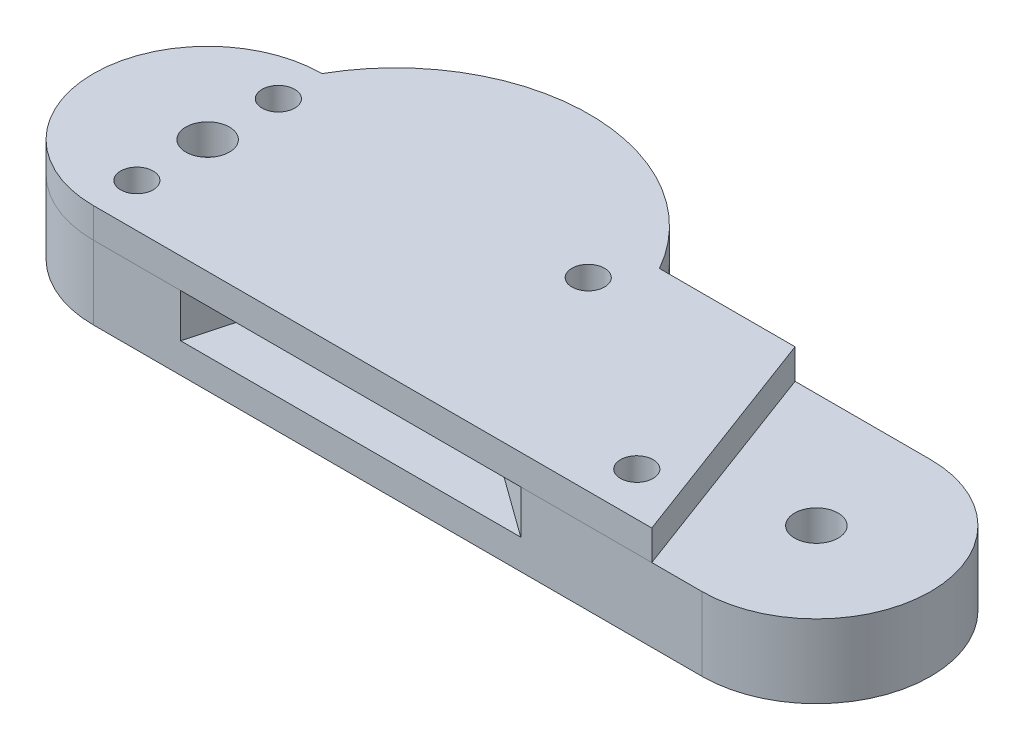
SolidWorks part; units mm, degrees
ref_plane "Front Plane" through (0, 0, 0) normal (0, 0, 1) x (1, 0, 0)
ref_plane "Top Plane" through (0, 0, 0) normal (0, 1, 0) x (1, 0, 0)
ref_plane "Right Plane" through (0, 0, 0) normal (1, 0, 0) x (0, 0, -1)
sketch "Sketch1" plane through (0, 0, 0) normal (0, 1, 0) x (1, 0, 0)
  line L0 (0, -10.5004) -> (-55.9305, -10.5004)
  line L1 (0, 10.5004) -> (-55.9305, 10.5004)
  line L5 (0, 11.5004) -> (-55.9305, 11.5004) construction
  line L6 (0, -11.5004) -> (-55.9305, -11.5004) construction
  circle A0 centre (0, 0) radius 2
  arc A1 (0, -10.5004) -> (0, 10.5004) centre (0, 0) ccw
  arc A2 (-55.9305, 10.5004) -> (-55.9305, -10.5004) centre (-55.9305, 0) ccw
  circle A3 centre (-55.9305, 0) radius 2
  arc A7 (0, -11.5004) -> (0, 11.5004) centre (0, 0) ccw construction
  arc A8 (-55.9305, 11.5004) -> (-55.9305, -11.5004) centre (-55.9305, 0) ccw construction
  arc A9 (-67.2423, -5.04) -> (-54.9145, -15.6487) centre (-55.7741, -4.1805) ccw construction
  arc A10 (-55.9305, 10.5004) -> (-55.9305, -10.5004) centre (-55.9305, 0) ccw construction
  circle A11 centre (0, 0) radius 67.4309 construction
  arc A12 (-59.8966, 30.973) -> (-67.2423, -5.04) centre (0, 0) ccw construction
  dimension "D1" = 4
  dimension "D2" = 1
  dimension "D3" = 4
extrude "Boss-Extrude1" add sketch "Sketch1" along normal mid plane 9.5
sketch "Sketch3" plane through (0, 0, 0) normal (0, 1, 0) x (1, 0, 0)
  line L0 (0, 0) -> (-47.1525, -15.3208) construction
  line L1 (0, 0) -> (24.7895, -42.9367) construction
  line L2 (0, 0) -> (-55.9305, 0) construction
  line L3 (24.7895, -42.9367) -> (-41.5934, 5.0595) construction
  line L4 (-41.5934, 5.0595) -> (-47.1525, -15.3208) construction
  line L5 (-41.5934, 5.0595) -> (-37.6461, 19.5308) construction
  line L6 (-41.5934, 5.0595) -> (-53.749, 13.8482) construction
  line L7 (22.8477, -44.0007) -> (-38.0092, 0) construction
  line L8 (-35.7518, 18.8753) -> (-39.2995, 5.869)
  line L9 (-43.8873, 4.25) -> (-54.8123, 12.149)
  line L11 (26.6452, -41.8104) -> (-39.2995, 5.869)
  line L12 (-39.6108, 19.9279) -> (-42.7627, 8.3729) construction
  line L13 (-42.7627, 8.3729) -> (-52.4686, 15.3905) construction
  line L14 (-40.9004, 0) -> (-45.9674, -18.5763) construction
  line L15 (-43.8873, 4.25) -> (-48.2065, -11.585)
  line L18 (-40.4216, 6.6802) -> (-50.8477, 14.2185) construction
  line L20 (-41.5934, 5.0595) -> (-52.0196, 12.5978) construction
  line L21 (-42.7652, 3.4387) -> (-53.1914, 10.977) construction
  line L23 (-43.5229, 5.5858) -> (-49.082, -14.7945) construction
  line L26 (-39.6639, 4.5332) -> (-45.223, -15.8471) construction
  line L27 (25.9613, -41.316) -> (-40.4216, 6.6802) construction
  line L28 (23.6177, -44.5574) -> (-42.7652, 3.4387) construction
  arc A1 (-48.2065, -11.585) -> (26.6452, -41.8104) centre (0, 0) ccw
  arc A4 (-55.9305, 10.5004) -> (-55.9305, -10.5004) centre (-55.9305, 0) ccw construction
  arc A7 (-35.7518, 18.8753) -> (-54.8123, 12.149) centre (-41.5934, 5.0595) ccw
  dimension "D1" = 99.1581
  dimension "D3" = 120
  dimension "D6" = 30
  dimension "D2" = 18
  dimension "D4" = 2
  dimension "D5" = 2
extrude "Cut-Extrude1" cut sketch "Sketch3" against normal mid plane 4
sketch "Sketch5" plane through (0, 0, 0) normal (0, 1, 0) x (1, 0, 0)
  line L0 (-40.4241, 1.7461) -> (-52.5322, 10.5004) construction
  line L1 (-40.4241, 1.7461) -> (-35.7382, 18.9254) construction
  line L2 (-52.5322, 10.5004) -> (-43.8873, 4.25) construction
  line L3 (-39.2995, 5.869) -> (-38.0362, 10.5004) construction
  line L4 (-55.9305, 10.5004) -> (-24.9177, 10.5004)
  line L5 (0, 10.5004) -> (-55.9305, 10.5004) construction
  circle A0 centre (-40.4241, 1.7461) radius 17.807
extrude "Boss-Extrude2" add sketch "Sketch5" along normal up to surface and the other way up to surface
sketch "Sketch6" plane through (0, 0, 0) normal (0, 1, 0) x (1, 0, 0)
  line L0 (-39.2995, 5.869) -> (-16.6593, -10.5004)
  line L1 (-47.9107, -10.5004) -> (-43.8873, 4.25)
  line L2 (-43.8873, 4.25) -> (-54.8544, 12.1794)
  line L3 (-39.2995, 5.869) -> (-35.7382, 18.9254)
  line L4 (-16.6593, -10.5004) -> (-39.2995, 5.869) construction
  line L5 (-43.8873, 4.25) -> (-47.9107, -10.5004) construction
  line L6 (-52.5322, 10.5004) -> (-43.8873, 4.25) construction
  line L7 (-39.2995, 5.869) -> (-38.0362, 10.5004) construction
  line L8 (-55.9305, -10.5004) -> (0, -10.5004) construction
  line L9 (-16.6593, -10.5004) -> (-47.9107, -10.5004)
  arc A0 (-24.9177, 10.5004) -> (-55.9305, 10.5004) centre (-40.4241, 1.7461) ccw construction
  arc A1 (-35.7382, 18.9254) -> (-54.8544, 12.1794) centre (-40.4241, 1.7461) ccw
extrude "Cut-Extrude2" cut sketch "Sketch6" against normal mid plane 4
sketch "Sketch7" plane through (0, -4.75, 0) normal (0, -1, 0) x (1, 0, 0)
  line L0 (0, 0) -> (4.5965, 4.5965) construction
  line L1 (0, 0) -> (6.5004, 0) construction
  line L4 (0, 6.5004) -> (-55.9305, 6.5004)
  line L5 (-27.4616, -6.5004) -> (0, -6.5004)
  line L6 (0, 6.5004) -> (-55.9305, 6.5004) construction
  line L7 (-55.9305, -6.5004) -> (0, -6.5004) construction
  circle A3 centre (-27.4616, -6.5004) radius 1.5
  circle A4 centre (0, -6.5004) radius 1.5 construction
  circle A5 centre (4.5965, 4.5965) radius 1.5 construction
  arc A6 (0, -6.5004) -> (0, 6.5004) centre (0, 0) ccw
  arc A7 (-55.9305, 6.5004) -> (-53.5442, -6.0466) centre (-55.9305, 0) ccw
  arc A8 (-53.5442, -6.0466) -> (-27.4616, -6.5004) centre (-40.4241, -1.7461) ccw
  arc A9 (0, -6.5004) -> (0, 6.5004) centre (0, 0) ccw construction
  arc A10 (-55.9305, 6.5004) -> (-53.5442, -6.0466) centre (-55.9305, 0) ccw construction
  arc A11 (-53.5442, -6.0466) -> (-27.4616, -6.5004) centre (-40.4241, -1.7461) ccw construction
  circle A12 centre (-10, 6.5004) radius 1.5
  circle A13 centre (-55.9305, 6.5004) radius 1.5
  circle A14 centre (-55.9305, -6.5004) radius 1.5
  dimension "D4" = 3
  dimension "D2" = 10
  dimension "D3" = 45
  dimension "D1" = 4
extrude "Cut-Extrude3" cut sketch "Sketch7" against normal through all
sketch "Sketch8" plane through (0, -4.75, 0) normal (0, -1, 0) x (1, 0, 0)
  circle A0 centre (-55.9305, 6.5004) radius 2.75
  circle A1 centre (-55.9305, -6.5004) radius 2.75
  circle A2 centre (-27.4616, -6.5004) radius 2.75
  circle A3 centre (-10, 6.5004) radius 2.75
  dimension "D1" = 5.5
extrude "Cut-Extrude4" cut sketch "Sketch8" against normal blind 3.2
ref_plane "Plane1" through (0, 2, 0) normal (0, -1, 0) x (-1, 0, 0)
sketch "Sketch9" plane through (0, 4.75, 0) normal (0, 1, 0) x (1, 0, 0)
  line L0 (-12.4589, 10.5004) -> (-4.6195, -10.5004)
  line L1 (0, 10.5004) -> (-24.9177, 10.5004) construction
  line L2 (-55.9305, -10.5004) -> (0, -10.5004) construction
  line L3 (-6.5881, -5.2268) -> (-10, -6.5004) construction
  line L4 (-4.6195, -10.5004) -> (0, -10.5004)
  line L5 (-12.4589, 10.5004) -> (0, 10.5004)
  circle A0 centre (0, 0) radius 8 construction
  circle A1 centre (-10, -6.5004) radius 1.5 construction
  circle A2 centre (-10, -6.5004) radius 1.5 construction
  arc A3 (0, -10.5004) -> (0, 10.5004) centre (0, 0) ccw
  arc A4 (0, -10.5004) -> (0, 10.5004) centre (0, 0) ccw construction
  dimension "D1" = 16
extrude "Cut-Extrude5" cut sketch "Sketch9" against normal up to surface (2.75 mm away)
split "Split1" trim tools "Plane1" bodies to split 113 resulting bodies 111 112
